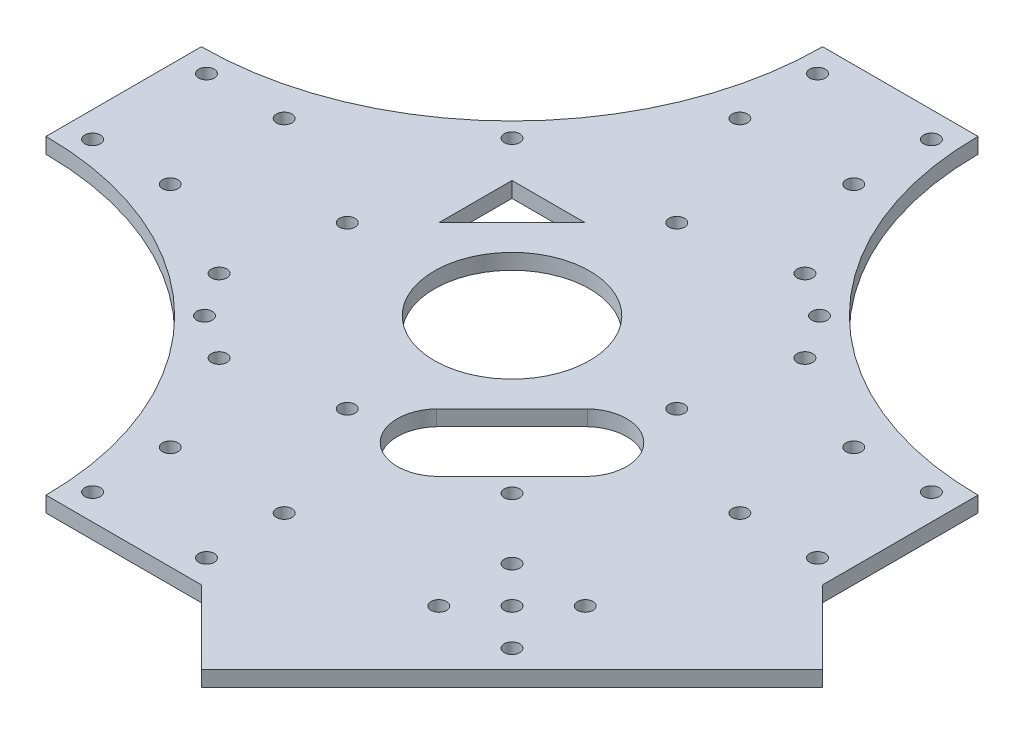
SolidWorks part; units mm, degrees
material "Hexcel AS4C (3000 丝)"
ref_plane "前视基准面" through (0, 0, 0) normal (0, 0, 1) x (1, 0, 0)
ref_plane "上视基准面" through (0, 0, 0) normal (0, 1, 0) x (1, 0, 0)
ref_plane "右视基准面" through (0, 0, 0) normal (1, 0, 0) x (0, 0, -1)
sketch "草图1" plane through (0, 0, 0) normal (0, 1, 0) x (1, 0, 0)
  line L0 (0, 0) -> (0, 75)
  line L1 (0, 0) -> (75, 0)
  line L2 (0, 0) -> (0, -75)
  line L3 (0, 0) -> (-75, 0)
  line L4 (0, 75) -> (15, 75)
  line L5 (0, 75) -> (-15, 75)
  line L6 (75, 0) -> (75, 15)
  line L7 (75, 0) -> (75, -15)
  line L8 (0, -75) -> (15, -75)
  line L9 (0, -75) -> (-15, -75)
  line L10 (-75, 0) -> (-75, -15)
  line L11 (-75, 0) -> (-75, 15)
  line L12 (75, 0) -> (70, 0)
  arc A0 (-75, 15) -> (-15, 75) centre (-75, 75) ccw
  arc A1 (15, 75) -> (75, 15) centre (75, 75) ccw
  arc A2 (75, -15) -> (15, -75) centre (75, -75) ccw
  arc A3 (-15, -75) -> (-75, -15) centre (-75, -75) ccw
  circle A4 centre (-11, 70) radius 1.25
  circle A5 centre (11, 70) radius 1.25
  circle A6 centre (70, -11) radius 1.25
  circle A7 centre (70, 11) radius 1.25
  circle A8 centre (-11, -70) radius 1.25
  circle A9 centre (11, -70) radius 1.25
  circle A10 centre (-70, 11) radius 1.25
  circle A11 centre (-70, -11) radius 1.25
  point P9 (0, 0)
  point P21 (0, 0)
  point P32 (0, 0)
  point P35 (0, 0)
  point P44 (0, 0)
  dimension "D1" = 4
extrude "凸台-拉伸1" add sketch "草图1" along normal blind 3 contours A2 L7 L1 L2 L8 A9 A6 | A3 L9 L2 L3 L10 A11 A8 | A0 L11 L3 L0 L5 A4 A10 | A1 L4 L0 L1 L6 A7 A5
sketch "草图2" plane through (0, 0, 0) normal (0, -1, 0) x (1, 0, 0)
  line L0 (0, 0) -> (-32.5736, -32.5736)
  line L1 (0, 0) -> (32.5736, -32.5736)
  line L2 (-31.4663, 0.3536) -> (-0.3536, 31.4663)
  line L3 (31.4663, -0.3536) -> (-0.3536, 31.4663)
  line L4 (0.3536, -31.4663) -> (31.4663, -0.3536)
  line L5 (0.3536, -31.4663) -> (-31.4663, 0.3536)
  arc A0 (-15, -75) -> (-75, -15) centre (-75, -75) ccw construction
  circle A2 centre (0.3536, -31.4663) radius 1.5
  circle A3 centre (31.4663, -0.3536) radius 1.5
  circle A4 centre (-0.3536, 31.4663) radius 1.5
  circle A5 centre (-31.4663, 0.3536) radius 1.5
  point P12 (-15.5563, -15.5563)
  point P16 (-15.9099, 15.9099)
  point P17 (15.9099, -15.9099)
extrude "切除-拉伸1" cut sketch "草图2" against normal blind 3 contours A3 | A2 | A5 | A4
sketch "草图3" plane through (0, 3, 0) normal (0, 1, 0) x (1, 0, 0)
  line L0 (0.3536, 31.4663) -> (-31.4663, -0.3536)
  line L1 (-15.5563, 15.5563) -> (-22.6274, 22.6274)
  line L2 (-15.5563, 15.5563) -> (-12.0208, 19.0919)
  line L3 (-15.5563, 15.5563) -> (-19.0919, 12.0208)
  line L4 (-19.0919, 12.0208) -> (-22.6274, 22.6274)
  line L5 (-12.0208, 19.0919) -> (-22.6274, 22.6274)
extrude "切除-拉伸2" cut sketch "草图3" against normal blind 3 contours L0 L5 L1 | L4 L0 L1
sketch "草图4" plane through (0, 3, 0) normal (0, 1, 0) x (1, 0, 0)
  line L0 (31.4663, 0.3536) -> (-0.3536, -31.4663)
  line L1 (0, 0) -> (21.2132, -21.2132)
  line L2 (28.2843, -14.1421) -> (14.1421, -28.2843)
  line L3 (14.1421, -28.2843) -> (28.2843, -14.1421) construction
  line L4 (8.4817, -22.6239) -> (22.6239, -8.4817)
  line L5 (19.8025, -33.9447) -> (33.9447, -19.8025)
  arc A0 (8.4817, -22.6239) -> (19.8025, -33.9447) centre (14.1421, -28.2843) ccw
  arc A1 (33.9447, -19.8025) -> (22.6239, -8.4817) centre (28.2843, -14.1421) ccw
  point P9 (21.2132, -21.2132)
extrude "切除-拉伸3" cut sketch "草图4" against normal blind 3
sketch "草图5" plane through (0, 3, 0) normal (0, 1, 0) x (1, 0, 0)
  line L0 (-12.0208, 19.0919) -> (-8.4853, 22.6274)
  line L1 (-8.4853, 22.6274) -> (-22.6274, 22.6274)
  line L2 (-19.0919, 12.0208) -> (-22.6274, 8.4853)
  line L3 (-22.6274, 8.4853) -> (-22.6274, 22.6274)
  line L4 (-12.0208, 19.0919) -> (-22.6274, 22.6274)
  line M28 (-19.0919, 12.0208) -> (-22.6274, 22.6274)
extrude "切除-拉伸4" cut sketch "草图5" against normal blind 10 contours L3 L2 M28 | L4 L0 L1
sketch "草图6" plane through (0, 3, 0) normal (0, 1, 0) x (1, 0, 0)
  line L0 (0, 0) -> (-28.2843, -28.2843)
  line L1 (-28.2843, -28.2843) -> (-35.3553, -21.2132)
  line L2 (0, 0) -> (-22.6274, 22.6274)
  circle A0 centre (-35.3553, -21.2132) radius 1.5
  circle A1 centre (-21.2132, -35.3553) radius 1.5
  circle A2 centre (35.3553, 21.2132) radius 1.5
  circle A3 centre (21.2132, 35.3553) radius 1.5
extrude "切除-拉伸5" cut sketch "草图6" against normal blind 10 contours A1 | A0 | A2 | A3
sketch "草图7" plane through (0, 3, 0) normal (0, 1, 0) x (1, 0, 0)
  circle A0 centre (-29.6985, 29.6985) radius 1.5
  circle A1 centre (29.6985, 29.6985) radius 1.5
  circle A2 centre (29.6985, -29.6985) radius 1.5
  circle A3 centre (-29.6985, -29.6985) radius 1.5
  point P11 (0, 0)
  dimension "D1" = 4
extrude "切除-拉伸8" cut sketch "草图7" against normal blind 10
sketch "草图8" plane through (0, 3, 0) normal (0, 1, 0) x (1, 0, 0)
  circle A0 centre (-11, 55) radius 1.5
  circle A1 centre (11, 55) radius 1.5
  circle A2 centre (55, 11) radius 1.5
  circle A3 centre (55, -11) radius 1.5
  circle A4 centre (11, -55) radius 1.5
  circle A5 centre (-11, -55) radius 1.5
  circle A6 centre (-55, -11) radius 1.5
  circle A7 centre (-55, 11) radius 1.5
  point P21 (0, 0)
  dimension "D1" = 4
extrude "切除-拉伸9" cut sketch "草图8" against normal blind 10
sketch "草图9" plane through (0, 3, 0) normal (0, 1, 0) x (1, 0, 0)
  circle A0 centre (0, 0) radius 15
extrude "切除-拉伸10" cut sketch "草图9" against normal blind 10
sketch "草图10" plane through (0, 3, 0) normal (0, 1, 0) x (1, 0, 0)
  line L0 (75, -15) -> (15, -75)
  line L1 (75, -15) -> (89.1421, -29.1421)
  line L2 (15, -75) -> (29.1421, -89.1421)
  line L3 (89.1421, -29.1421) -> (29.1421, -89.1421)
  circle A0 centre (75, -75) radius 60
  arc M31 (15, -75) -> (75, -15) centre (75, -75) cw
extrude "凸台-拉伸2" add sketch "草图10" against normal blind 3 contours L3 L1 L0 L2 | L0 M31
sketch "草图11" plane through (0, 3, 0) normal (0, 1, 0) x (1, 0, 0)
  circle A0 centre (11, 70) radius 1.5
  circle A1 centre (-11, 70) radius 1.5
  circle A2 centre (70, 11) radius 1.5
  circle A3 centre (70, -11) radius 1.5
  circle A4 centre (11, -70) radius 1.5
  circle A5 centre (-11, -70) radius 1.5
  circle A6 centre (-70, -11) radius 1.5
  circle A7 centre (-70, 11) radius 1.5
  point P21 (0, 0)
  dimension "D1" = 4
extrude "切除-拉伸11" cut sketch "草图11" against normal blind 3
sketch "草图12" plane through (0, 3, 0) normal (0, 1, 0) x (1, 0, 0)
  circle A0 centre (48.5355, -48.5355) radius 1.5
  circle A1 centre (55.6066, -41.4645) radius 1.5
  circle A2 centre (55.6066, -55.6066) radius 1.5
  circle A3 centre (41.4645, -55.6066) radius 1.5
  circle A4 centre (41.4645, -41.4645) radius 1.5
  point P16 (48.5355, -48.5355)
  dimension "D1" = 4
extrude "切除-拉伸12" cut sketch "草图12" against normal blind 3
